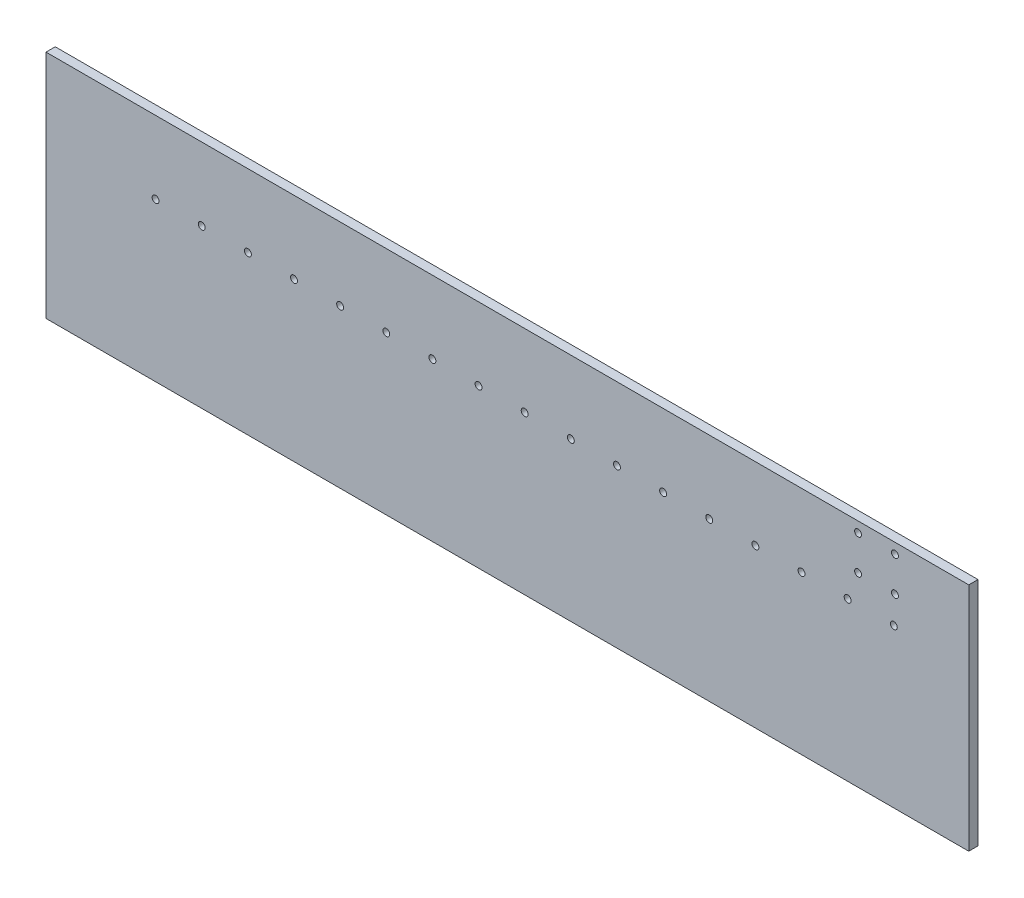
SolidWorks part; units mm, degrees
material "Thornel Mat VMA"
ref_plane "前视基准面" through (0, 0, 0) normal (0, 0, 1) x (1, 0, 0)
ref_plane "上视基准面" through (0, 0, 0) normal (0, 1, 0) x (1, 0, 0)
ref_plane "右视基准面" through (0, 0, 0) normal (1, 0, 0) x (0, 0, -1)
sketch "草图1" plane through (0, 0, 0) normal (0, 0, 1) x (1, 0, 0)
  line L1 (0, 0) -> (400, 0)
  line L2 (0, 0) -> (0, 100)
  line L3 (0, 100) -> (400, 100)
  line L4 (400, 0) -> (400, 100)
  dimension "D1" = 400
  dimension "D2" = 100
extrude "凸台-拉伸1" add sketch "草图1" along normal blind 4
sketch "草图2" plane through (0, 0, 0) normal (0, 0, -1) x (-1, 0, 0)
  line L0 (-400, 100) -> (0, 100) construction
  line L1 (-368, 95.5) -> (-352, 95.5) construction
  line L2 (-368, 95.5) -> (-368, 80.5) construction
  line L3 (-368, 80.5) -> (-352, 80.5) construction
  line L4 (-352, 95.5) -> (-352, 80.5) construction
  line L5 (-400, 0) -> (-400, 100) construction
  circle A0 centre (-368, 95.5) radius 1.5
  circle A1 centre (-352, 95.5) radius 1.5
  circle A2 centre (-368, 80.5) radius 1.5
  circle A3 centre (-352, 80.5) radius 1.5
  dimension "D5" = 3
  dimension "D6" = 3
  dimension "D7" = 3
  dimension "D8" = 3
  dimension "D1" = 16
  dimension "D2" = 15
  dimension "D3" = 4.5
  dimension "D4" = 32
extrude "切除-拉伸1" cut sketch "草图2" against normal blind 4
sketch "草图3" plane through (0, 0, 0) normal (0, 0, -1) x (-1, 0, 0)
  line L0 (-400, 0) -> (-400, 100) construction
  circle A0 centre (-367.5, 68.5) radius 1.5
  dimension "D2" = 3
  dimension "D1" = 32.5
extrude "切除-拉伸2" cut sketch "草图3" against normal blind 4
pattern_linear "阵列(线性)1" count 17 spacing 20 along (-1, 0, 0) of "切除-拉伸2"
